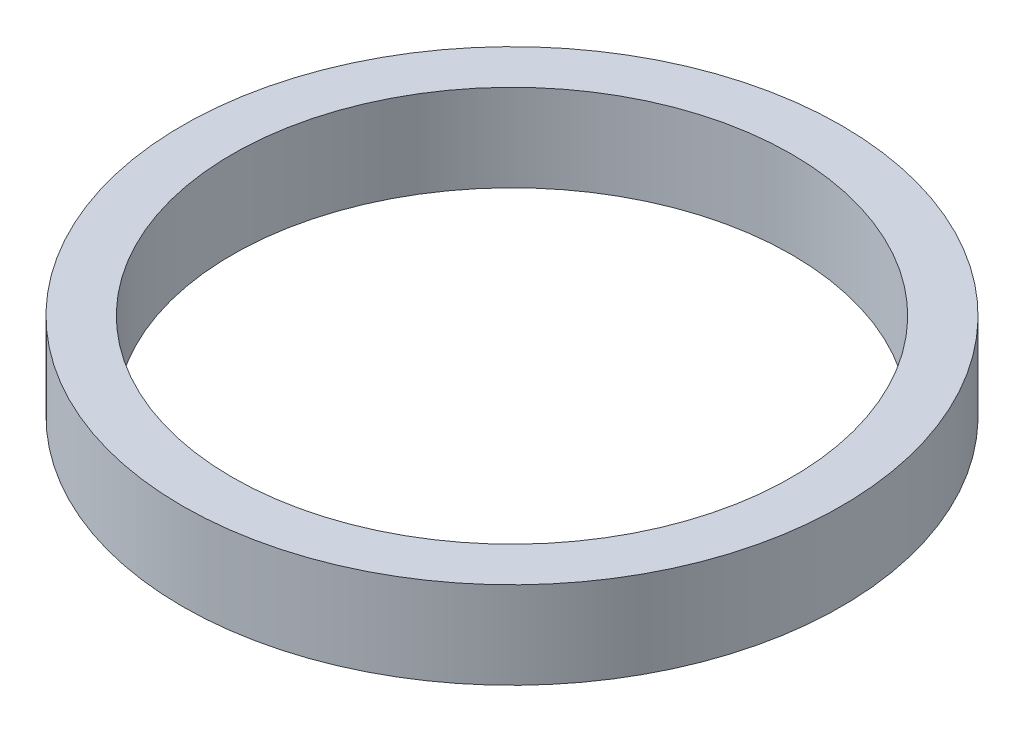
SolidWorks part; units mm, degrees
ref_plane "Front Plane" through (0, 0, 0) normal (0, 0, 1) x (1, 0, 0)
ref_plane "Top Plane" through (0, 0, 0) normal (0, 1, 0) x (1, 0, 0)
ref_plane "Right Plane" through (0, 0, 0) normal (1, 0, 0) x (0, 0, -1)
sketch "Sketch1" plane through (0, 0, 0) normal (0, 1, 0) x (1, 0, 0)
  circle A0 centre (0, 0) radius 45
  circle A1 centre (0, 0) radius 53
  dimension "D1" = 106
  dimension "D2" = 90
extrude "Boss-Extrude1" add sketch "Sketch1" along normal blind 14
sketch "Sketch2" plane through (0, 0, 0) normal (0, -1, 0) x (1, 0, 0)
  line L0 (0, 0) -> (0, 49) construction
  circle A0 centre (0, 49) radius 2.4
  circle A1 centre (42.4352, 24.5) radius 2.4
  circle A2 centre (42.4352, -24.5) radius 2.4
  circle A3 centre (0, -49) radius 2.4
  circle A4 centre (-42.4352, -24.5) radius 2.4
  circle A5 centre (-42.4352, 24.5) radius 2.4
  point P10 (0, 0)
  dimension "D1" = 4.8
  dimension "D2" = 49
  dimension "D3" = 6
extrude "Cut-Extrude1" cut sketch "Sketch2" against normal blind 4
sketch "Sketch3" plane through (0, 0, 0) normal (0, -1, 0) x (1, 0, 0)
  circle A0 centre (0, 49) radius 1.6
  circle A1 centre (42.4352, 24.5) radius 1.6
  circle A2 centre (42.4352, -24.5) radius 1.6
  circle A3 centre (0, -49) radius 1.6
  circle A4 centre (-42.4352, 24.5) radius 1.6
  circle A5 centre (-42.4352, -24.5) radius 1.6
  dimension "D1" = 3.2
extrude "Cut-Extrude2" cut sketch "Sketch3" against normal blind 6
